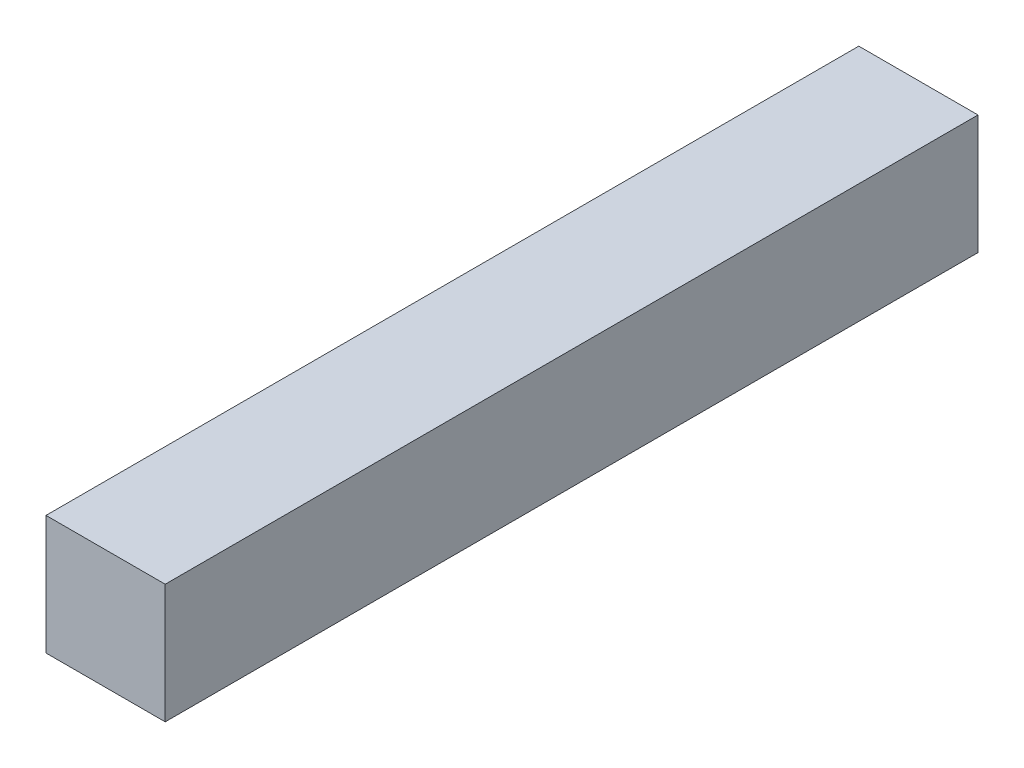
SolidWorks part; units mm, degrees
ref_plane "Front Plane" through (0, 0, 0) normal (0, 0, 1) x (1, 0, 0)
ref_plane "Top Plane" through (0, 0, 0) normal (0, 1, 0) x (1, 0, 0)
ref_plane "Right Plane" through (0, 0, 0) normal (1, 0, 0) x (0, 0, -1)
sketch "Sketch1" plane through (0, 0, 0) normal (0, 0, 1) x (1, 0, 0)
  line L1 (-11, 11) -> (11, 11)
  line L2 (-11, 11) -> (-11, -11)
  line L3 (-11, -11) -> (11, -11)
  line L4 (11, 11) -> (11, -11)
  line L5 (-11, 11) -> (11, -11) construction
  line L6 (-11, -11) -> (11, 11) construction
  point P0 (0, 0)
  dimension "D1" = 22
  dimension "D2" = 22
extrude "Boss-Extrude1" add sketch "Sketch1" along normal blind 150
